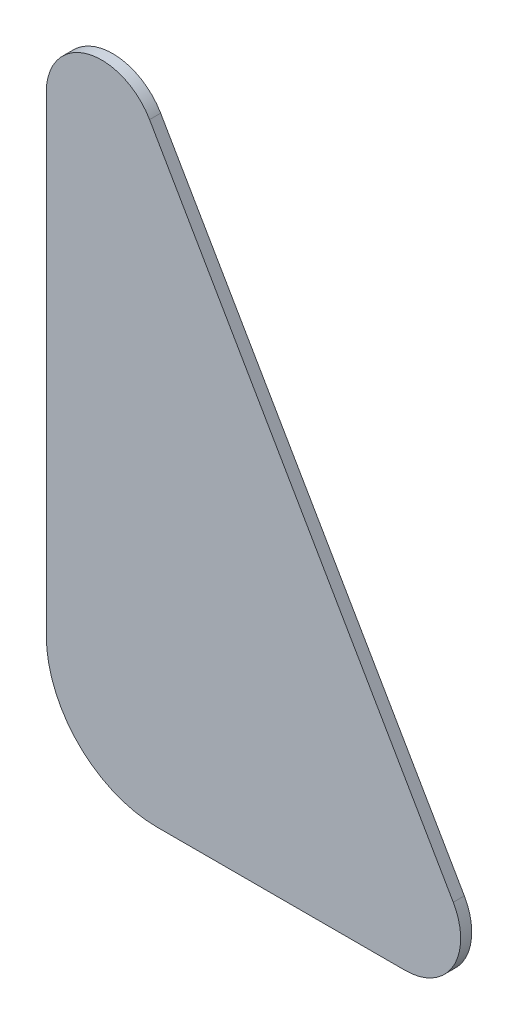
SolidWorks part; units mm, degrees
ref_plane "Front Plane" through (0, 0, 0) normal (0, 0, 1) x (1, 0, 0)
ref_plane "Top Plane" through (0, 0, 0) normal (0, 1, 0) x (1, 0, 0)
ref_plane "Right Plane" through (0, 0, 0) normal (1, 0, 0) x (0, 0, -1)
sketch "Sketch1" plane through (0, 0, 0) normal (0, 0, 1) x (1, 0, 0)
  line L0 (0, 100) -> (0, 525)
  line L1 (93.3013, 550) -> (367.5426, 75)
  line L2 (324.2414, 0) -> (100, 0)
  line L3 (-290.1416, 575) -> (615.7293, 575) construction
  arc A0 (0, 100) -> (100, 0) centre (100, 100) ccw
  arc A1 (0, 525) -> (93.3013, 550) centre (50, 525) cw
  arc A2 (367.5426, 75) -> (324.2414, 0) centre (324.2414, 50) cw
  point P3 (0, 0)
  point P8 (0, 0)
  point P11 (0, 711.6025)
  dimension "D2" = 100
  dimension "D3" = 50
  dimension "D1" = 575
  dimension "D4" = 60
extrude "Boss-Extrude1" add sketch "Sketch1" along normal blind 10
